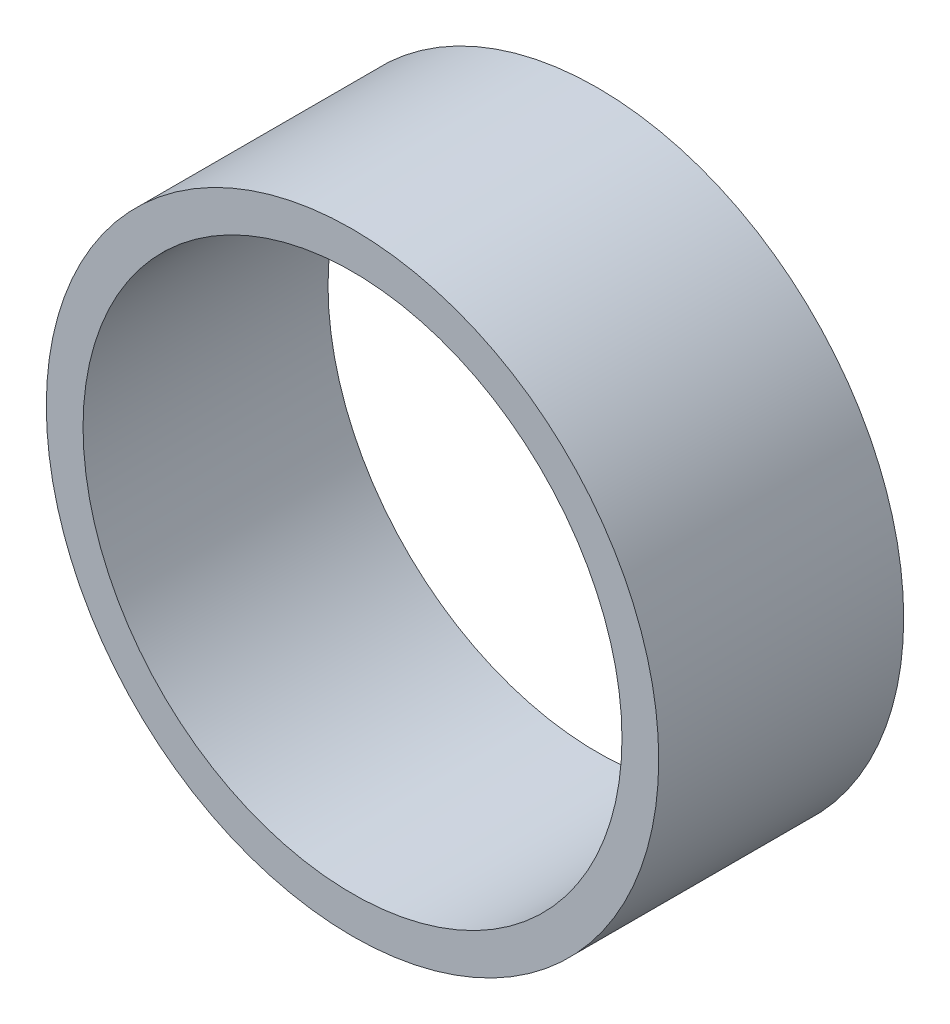
SolidWorks part; units mm, degrees
material "Acrylic (Medium-high impact)"
ref_plane "Front Plane" through (0, 0, 0) normal (0, 0, 1) x (1, 0, 0)
ref_plane "Top Plane" through (0, 0, 0) normal (0, 1, 0) x (1, 0, 0)
ref_plane "Right Plane" through (0, 0, 0) normal (1, 0, 0) x (0, 0, -1)
sketch "Sketch1" plane through (0, 0, 0) normal (0, 0, 1) x (1, 0, 0)
  circle A0 centre (0, 0) radius 25
  circle A1 centre (0, 0) radius 22
  dimension "D1" = 44
  dimension "D2" = 50
extrude "Boss-Extrude1" add sketch "Sketch1" along normal blind 20
